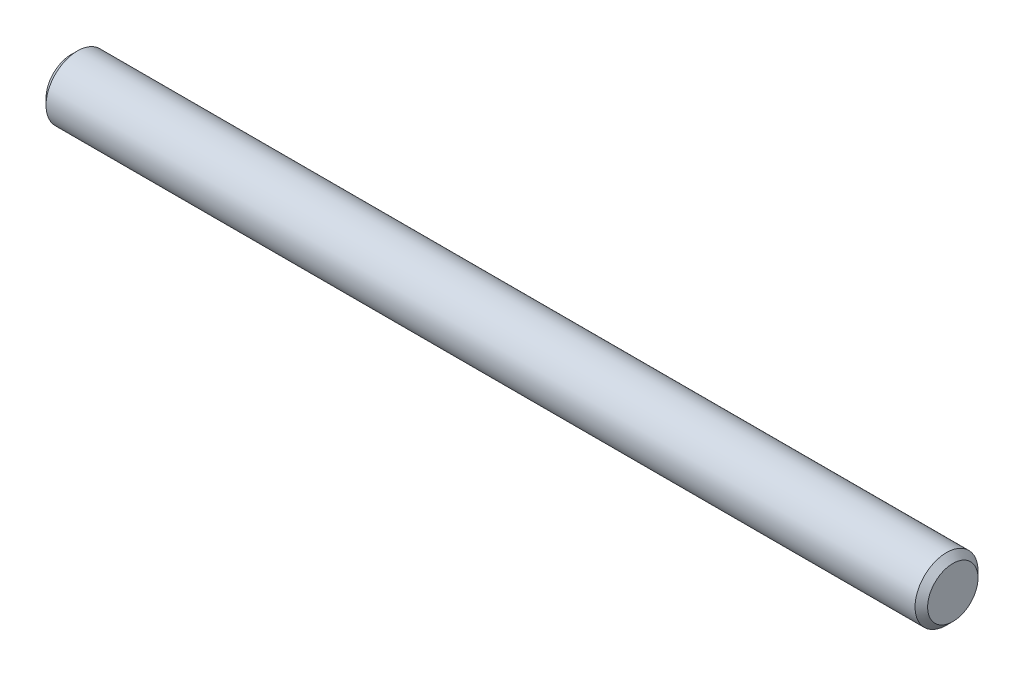
SolidWorks part; units mm, degrees
ref_plane "Front" through (0, 0, 0) normal (0, 0, 1) x (1, 0, 0)
ref_plane "Top" through (0, 0, 0) normal (0, 1, 0) x (1, 0, 0)
ref_plane "Right" through (0, 0, 0) normal (1, 0, 0) x (0, 0, -1)
sketch "Sketch1" plane through (0, 0, 0) normal (0, 0, 1) x (1, 0, 0)
  line L0 (-11.1125, 0) -> (11.1125, 0) construction
  line L1 (11.1125, 0.7937) -> (11.1125, -0.7937) construction
  line L2 (-11.1125, 0.7937) -> (-11.1125, -0.7937) construction
  dimension "Length" = 22.225
  dimension "Diameter" = 1.5875
sketch "Sketch2" plane through (0, 0, 0) normal (1, 0, 0) x (0, 0, -1)
  circle A0 centre (0, 0) radius 0.7937
extrude "Extrude1" add sketch "Sketch2" against normal up to vertex (11.1125 mm away) and the other way up to vertex (11.1125 mm away) up to point (-11.1125, 0.7937, 0) other way up to point (11.1125, 0.7937, 0)
chamfer "Chamfer1" distance 0.1588 angle 45 2 edges at (11.1125, 0, -0.7937) (-11.1125, 0, -0.7937)
equation "\"D1@Chamfer1\" = \"Diameter@Sketch1\"*.1"
